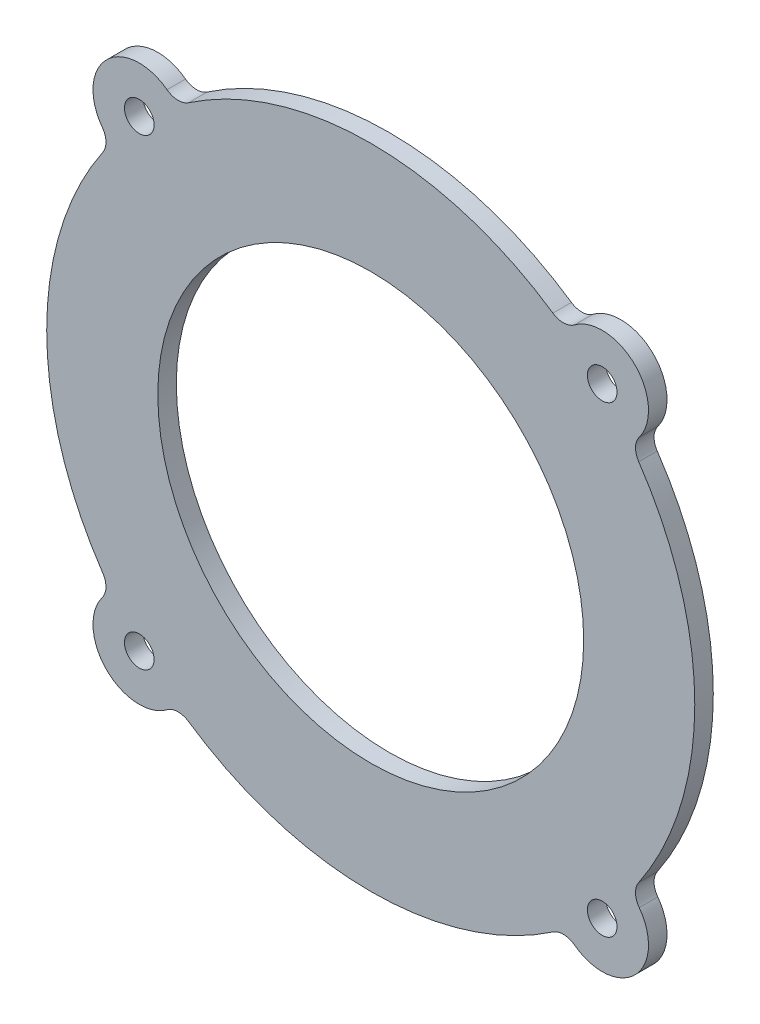
SolidWorks part; units mm, degrees
ref_plane "Front Plane" through (0, 0, 0) normal (0, 0, 1) x (1, 0, 0)
ref_plane "Top Plane" through (0, 0, 0) normal (0, 1, 0) x (1, 0, 0)
ref_plane "Right Plane" through (0, 0, 0) normal (1, 0, 0) x (0, 0, -1)
sketch "Sketch1" plane through (0, 0, 0) normal (0, 0, 1) x (1, 0, 0)
  circle A1 centre (0, 0) radius 23
  arc A2 (-28.9459, 19.6757) -> (-28.9459, -19.6757) centre (0, 0) ccw
  arc A3 (29, 22) -> (22, 29) centre (25, 25) ccw
  arc A5 (-29, -22) -> (-22, -29) centre (-25, -25) ccw
  arc A6 (22, -29) -> (29, -22) centre (25, -25) ccw
  circle A7 centre (-25, 25) radius 1.6
  circle A8 centre (25, 25) radius 1.6
  circle A9 centre (-25, -25) radius 1.6
  circle A10 centre (25, -25) radius 1.6
  arc A11 (-28.9459, -19.6757) -> (-29, -22) centre (-30.6, -20.8) cw
  arc A12 (-22, 29) -> (-29, 22) centre (-25, 25) ccw
  arc A13 (19.6757, 28.9459) -> (-19.6757, 28.9459) centre (0, 0) ccw
  arc A14 (-22, -29) -> (-19.6757, -28.9459) centre (-20.8, -30.6) cw
  arc A15 (-19.6757, -28.9459) -> (19.6757, -28.9459) centre (0, 0) ccw
  arc A16 (28.9459, -19.6757) -> (28.9459, 19.6757) centre (0, 0) ccw
  arc A17 (19.6757, -28.9459) -> (22, -29) centre (20.8, -30.6) cw
  arc A18 (29, -22) -> (28.9459, -19.6757) centre (30.6, -20.8) cw
  arc A19 (28.9459, 19.6757) -> (29, 22) centre (30.6, 20.8) cw
  arc A20 (22, 29) -> (19.6757, 28.9459) centre (20.8, 30.6) cw
  arc A21 (-28.9459, 19.6757) -> (-29, 22) centre (-30.6, 20.8) ccw
  arc A22 (-19.6757, 28.9459) -> (-22, 29) centre (-20.8, 30.6) cw
  point P20 (-21, -28)
  point P27 (28, -21)
  point P33 (21, 28)
  dimension "D1" = 46
  dimension "D5" = 70
  dimension "D6" = 3.2
  dimension "D7" = 3.2
  dimension "D8" = 3.2
  dimension "D9" = 3.2
  dimension "D10" = 10
  dimension "D11" = 50
  dimension "D12" = 10
  dimension "D13" = 10
  dimension "D14" = 5
  dimension "D15" = 2
  dimension "D2" = 50
  dimension "D3" = 50
  dimension "D4" = 50
extrude "Boss-Extrude1" add sketch "Sketch1" along normal blind 2
